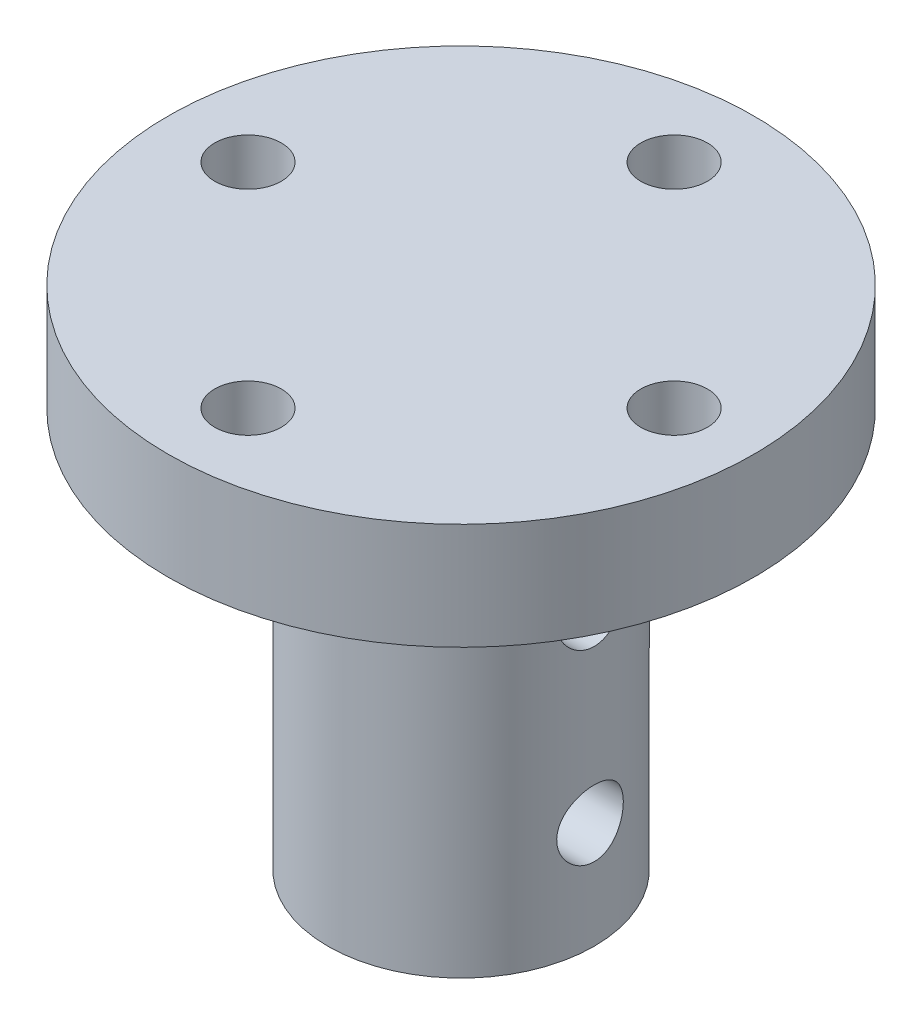
SolidWorks part; units mm, degrees
ref_plane "Front Plane" through (0, 0, 0) normal (0, 0, 1) x (1, 0, 0)
ref_plane "Top Plane" through (0, 0, 0) normal (0, 1, 0) x (1, 0, 0)
ref_plane "Right Plane" through (0, 0, 0) normal (1, 0, 0) x (0, 0, -1)
sketch "Sketch1" plane through (0, 0, 0) normal (0, 1, 0) x (1, 0, 0)
  line L0 (0, 11) -> (0, -11) construction
  line L1 (-11, 0) -> (11, 0) construction
  circle A0 centre (0, 0) radius 11
  circle A1 centre (0, 0) radius 8 construction
  dimension "D1" = 22
  dimension "D2" = 16
extrude "Boss-Extrude1" add sketch "Sketch1" along normal blind 4
sketch "Sketch2" plane through (0, 0, 0) normal (0, -1, 0) x (1, 0, 0)
  line L0 (-11, 0) -> (11, 0) construction
  line L1 (0, 11) -> (0, -11) construction
  circle A0 centre (0, 0) radius 8 construction
  circle A1 centre (0, 0) radius 11 construction
  circle A2 centre (0, -8) radius 1.25
  circle A3 centre (-8, 0) radius 1.25
  circle A4 centre (0, 8) radius 1.25
  circle A5 centre (8, 0) radius 1.25
  dimension "D1" = 16
  dimension "D2" = 2.5
  dimension "D3" = 2.5
  dimension "D4" = 2.5
  dimension "D5" = 2.5
sketch "Sketch5" plane through (0, 0, 0) normal (0, -1, 0) x (1, 0, 0)
  line L0 (-11, 0) -> (11, 0) construction
  line L1 (0, -11) -> (0, 11) construction
  circle A0 centre (0, 0) radius 11 construction
  circle A1 centre (0, 0) radius 2
  circle A2 centre (0, 0) radius 5
  dimension "D2" = 4
  dimension "D1" = 3
extrude "Boss-Extrude2" add sketch "Sketch5" along normal blind 15
ref_plane "Plane2" through (5, 0, 0) normal (1, 0, 0) x (0, 0, -1)
sketch "Sketch20" plane through (5, 0, 0) normal (1, 0, 0) x (0, 0, -1)
  line L0 (-5, -15) -> (5, -15) construction
  circle A0 centre (0, -4) radius 1.25
  circle A1 centre (0, -11) radius 1.25
  point P0 (0, -4)
  point P1 (0, -11)
  dimension "D3" = 2.5
  dimension "D4" = 2.5
  dimension "D1" = 4
  dimension "D2" = 4
extrude "Cut-Extrude1" cut sketch "Sketch2" against normal blind 10
extrude "Cut-Extrude2" cut sketch "Sketch20" against normal blind 4
